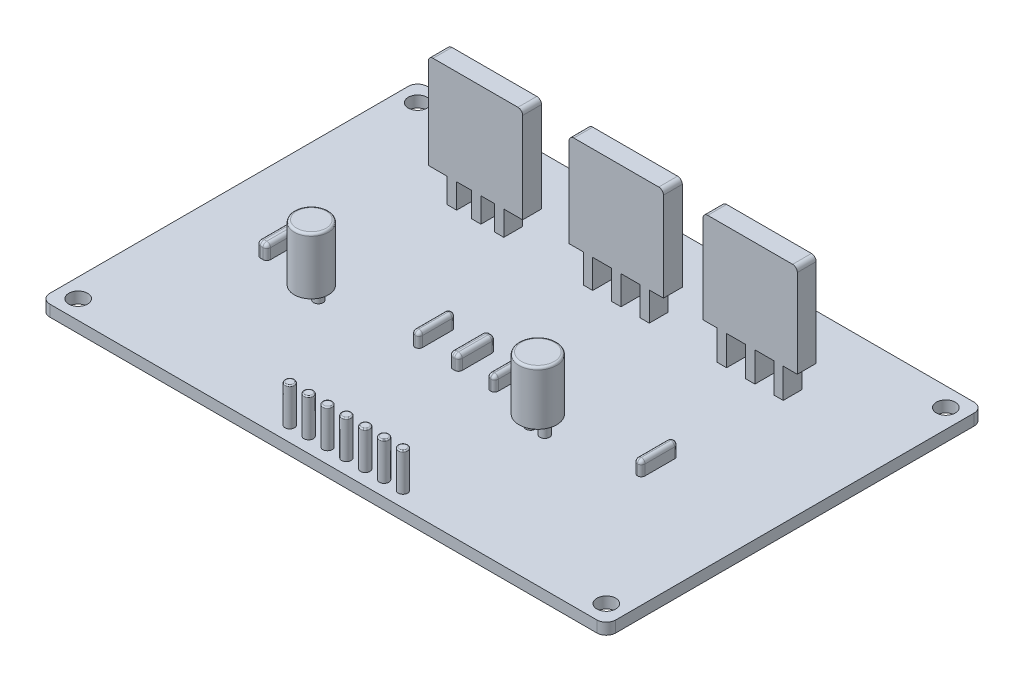
SolidWorks part; units mm, degrees
ref_plane "Front Plane" through (0, 0, 0) normal (0, 0, 1) x (1, 0, 0)
ref_plane "Top Plane" through (0, 0, 0) normal (0, 1, 0) x (1, 0, 0)
ref_plane "Right Plane" through (0, 0, 0) normal (1, 0, 0) x (0, 0, -1)
sketch "Sketch2" plane through (0, 0, 0) normal (0, 1, 0) x (1, 0, 0)
  line L1 (-30, -20) -> (30, -20)
  line L2 (-30, -20) -> (-30, 20)
  line L3 (-30, 20) -> (30, 20)
  line L4 (30, -20) -> (30, 20)
  line L5 (-30, -20) -> (30, 20) construction
  line L6 (-30, 20) -> (30, -20) construction
  point P0 (0, 0)
  dimension "D1" = 40
  dimension "D2" = 60
extrude "Boss-Extrude1" add sketch "Sketch2" along normal blind 1.2
sketch "Sketch3" plane through (0, 1.2, 0) normal (0, 1, 0) x (1, 0, 0)
  line L0 (-30, -20) -> (30, -20) construction
  line L1 (-30, 20) -> (-30, -20) construction
  line L2 (30, 20) -> (-30, 20) construction
  line L3 (30, -20) -> (30, 20) construction
  line L4 (30, 20) -> (-30, 20) construction
  circle A0 centre (-28, -18) radius 1
  circle A1 centre (-28, 18) radius 1
  circle A2 centre (28, 18) radius 1
  circle A3 centre (28, -18) radius 1
  dimension "D1" = 2
  dimension "D3" = 2
  dimension "D2" = 2
  dimension "D4" = 2
  dimension "D5" = 2
  dimension "D6" = 2
  dimension "D7" = 2
  dimension "D8" = 2
extrude "Cut-Extrude1" cut sketch "Sketch3" against normal blind 2
sketch "Sketch4" plane through (0, 1.2, 0) normal (0, 1, 0) x (1, 0, 0)
  line L1 (-19.065, 12.1957) -> (-9.065, 12.1957)
  line L2 (-19.065, 12.1957) -> (-19.065, 10.1957)
  line L3 (-19.065, 10.1957) -> (-9.065, 10.1957)
  line L4 (-9.065, 12.1957) -> (-9.065, 10.1957)
  line L5 (-19.065, 12.1957) -> (-9.065, 10.1957) construction
  line L6 (-19.065, 10.1957) -> (-9.065, 12.1957) construction
  point P0 (-14.065, 11.1957)
  dimension "D1" = 2
  dimension "D2" = 10
extrude "Boss-Extrude2" add sketch "Sketch4" along normal blind 12.6957 contours L3 L4 L1 L2
sketch "Sketch5" plane through (0, 0, -10.1957) normal (0, 0, 1) x (1, 0, 0)
  line L0 (-19.065, 1.2) -> (-9.065, 1.2) construction
  line L1 (-19.065, 1.2) -> (-17.065, 1.2)
  line L2 (-19.065, 1.2) -> (-19.065, 3.8072)
  line L3 (-19.065, 3.8072) -> (-17.065, 3.8072)
  line L4 (-17.065, 1.2) -> (-17.065, 3.8072)
  line L5 (-9.065, 1.2) -> (-11.065, 1.2)
  line L6 (-9.065, 1.2) -> (-9.065, 3.8072)
  line L7 (-9.065, 3.8072) -> (-11.065, 3.8072)
  line L8 (-11.065, 1.2) -> (-11.065, 3.8072)
  line L9 (-16.065, 3.8072) -> (-14.4903, 3.8072)
  line L10 (-16.065, 3.8072) -> (-16.065, 1.2)
  line L11 (-16.065, 1.2) -> (-14.4903, 1.2)
  line L12 (-14.4903, 3.8072) -> (-14.4903, 1.2)
  line L14 (-13.4903, 3.8072) -> (-12.065, 3.8072)
  line L15 (-13.4903, 3.8072) -> (-13.4903, 1.2)
  line L16 (-13.4903, 1.2) -> (-12.065, 1.2)
  line L17 (-12.065, 3.8072) -> (-12.065, 1.2)
  dimension "D1" = 1
  dimension "D2" = 1
  dimension "D3" = 1
  dimension "D4" = 2
  dimension "D5" = 2
extrude "Cut-Extrude2" cut sketch "Sketch5" against normal blind 3
sketch "Sketch6" plane through (0, 1.2, 0) normal (0, 1, 0) x (1, 0, 0)
  line L2 (-3.9751, 10.0333) -> (6.0249, 10.0333)
  line L3 (-3.9751, 10.0333) -> (-3.9751, 12.0333)
  line L4 (-3.9751, 12.0333) -> (6.0249, 12.0333)
  line L5 (6.0249, 10.0333) -> (6.0249, 12.0333)
  line L6 (10.2218, 10.0333) -> (20.2218, 10.0333)
  line L7 (10.2218, 10.0333) -> (10.2218, 12.0333)
  line L8 (10.2218, 12.0333) -> (20.2218, 12.0333)
  line L9 (20.2218, 10.0333) -> (20.2218, 12.0333)
  dimension "D1" = 2
  dimension "D2" = 10
  dimension "D3" = 2
  dimension "D4" = 10
extrude "Boss-Extrude3" add sketch "Sketch6" along normal blind 13 contours L6 L9 L8 L7 | L2 L5 L4 L3
sketch "Sketch7" plane through (0, 0, -10.0333) normal (0, 0, 1) x (1, 0, 0)
  line L0 (-3.9751, 1.2) -> (6.0249, 1.2) construction
  line L1 (-3.9751, 1.2) -> (-2.4751, 1.2)
  line L2 (-3.9751, 1.2) -> (-3.9751, 4.2459)
  line L3 (-3.9751, 4.2459) -> (-2.4751, 4.2459)
  line L4 (-2.4751, 1.2) -> (-2.4751, 4.2459)
  line L5 (-3.9751, 14.2) -> (-3.9751, 1.2) construction
  line L7 (6.0249, 1.2) -> (4.5249, 1.2)
  line L8 (6.0249, 1.2) -> (6.0249, 4.2459)
  line L9 (6.0249, 4.2459) -> (4.5249, 4.2459)
  line L10 (4.5249, 1.2) -> (4.5249, 4.2459)
  line L11 (-1.4751, 1.2) -> (0.5249, 1.2)
  line L12 (-1.4751, 1.2) -> (-1.4751, 4.2459)
  line L13 (-1.4751, 4.2459) -> (0.5249, 4.2459)
  line L14 (0.5249, 1.2) -> (0.5249, 4.2459)
  line L15 (1.5249, 1.2) -> (3.5249, 1.2)
  line L16 (1.5249, 1.2) -> (1.5249, 4.2459)
  line L17 (1.5249, 4.2459) -> (3.5249, 4.2459)
  line L18 (3.5249, 1.2) -> (3.5249, 4.2459)
  dimension "D1" = 1
  dimension "D2" = 1
  dimension "D3" = 1
  dimension "D4" = 1.5
  dimension "D5" = 1.5
  dimension "D6" = 2
  dimension "D7" = 2
extrude "Cut-Extrude3" cut sketch "Sketch7" against normal blind 3 contours L9 L10 L7 L8 | L13 L14 L11 L12 | L3 L4 L1 L2 | L17 L18 L15 L16
sketch "Sketch8" plane through (0, 0, -10.0333) normal (0, 0, 1) x (1, 0, 0)
  line L0 (10.2218, 1.2) -> (20.2218, 1.2) construction
  line L1 (10.2218, 1.2) -> (11.7218, 1.2)
  line L2 (10.2218, 1.2) -> (10.2218, 4.3532)
  line L3 (10.2218, 4.3532) -> (11.7218, 4.3532)
  line L4 (11.7218, 1.2) -> (11.7218, 4.3532)
  line L5 (20.2218, 1.2) -> (18.7218, 1.2)
  line L6 (20.2218, 1.2) -> (20.2218, 4.3532)
  line L7 (20.2218, 4.3532) -> (18.7218, 4.3532)
  line L8 (18.7218, 1.2) -> (18.7218, 4.3532)
  line L9 (17.7218, 1.2) -> (15.7218, 1.2)
  line L10 (17.7218, 1.2) -> (17.7218, 4.3532)
  line L11 (17.7218, 4.3532) -> (15.7218, 4.3532)
  line L12 (15.7218, 1.2) -> (15.7218, 4.3532)
  line L14 (14.7218, 1.2) -> (12.7218, 1.2)
  line L15 (14.7218, 1.2) -> (14.7218, 4.3532)
  line L16 (14.7218, 4.3532) -> (12.7218, 4.3532)
  line L17 (12.7218, 1.2) -> (12.7218, 4.3532)
  dimension "D1" = 1.5
  dimension "D2" = 1
  dimension "D3" = 1
  dimension "D4" = 1
  dimension "D5" = 2
  dimension "D6" = 2
extrude "Cut-Extrude4" cut sketch "Sketch8" against normal blind 3
sketch "Sketch9" plane through (0, 1.2, 0) normal (0, 1, 0) x (1, 0, 0)
  circle A0 centre (-16.6457, -5.3882) radius 0.5
  circle A1 centre (-15.1457, -5.3882) radius 0.5
  dimension "D1" = 1.5
extrude "Boss-Extrude5" add sketch "Sketch9" along normal blind 1
sketch "Sketch10" plane through (0, 2.2, 0) normal (0, 1, 0) x (1, 0, 0)
  circle A0 centre (-15.8957, -5.3772) radius 1.8145
extrude "Boss-Extrude6" add sketch "Sketch10" along normal blind 6
sketch "Sketch11" plane through (0, 1.2, 0) normal (0, 1, 0) x (1, 0, 0)
  circle A0 centre (7.7199, -5.7474) radius 0.5
  circle A1 centre (9.2199, -5.7474) radius 0.5
  dimension "D1" = 1.5
extrude "Boss-Extrude7" add sketch "Sketch11" along normal blind 1.5
sketch "Sketch12" plane through (0, 2.7, 0) normal (0, 1, 0) x (1, 0, 0)
  circle A0 centre (8.4536, -5.7145) radius 2
extrude "Boss-Extrude9" add sketch "Sketch12" along normal blind 5.7
sketch "Sketch13" plane through (0, 1.2, 0) normal (0, 1, 0) x (1, 0, 0)
  circle A0 centre (-5.1698, -18.3916) radius 0.5
  circle A1 centre (-3.1698, -18.3916) radius 0.5
  circle A2 centre (-1.1698, -18.3916) radius 0.5
  circle A3 centre (0.8302, -18.3916) radius 0.5
  circle A4 centre (2.8302, -18.3916) radius 0.5
  circle A5 centre (4.8302, -18.3916) radius 0.5
  circle A6 centre (6.8302, -18.3916) radius 0.5
  dimension "D1" = 2
  dimension "D2" = 2
  dimension "D3" = 2
  dimension "D4" = 2
  dimension "D5" = 2
  dimension "D6" = 2
extrude "Boss-Extrude10" add sketch "Sketch13" along normal blind 4
fillet "Fillet1" radius 1 4 edges at (-30, 0.6, -20) (30, 0.6, -20) (30, 0.6, 20) (-30, 0.6, 20)
fillet "Fillet2" radius 0.5 6 edges at (20.2218, 14.2, -11.0333) (10.2218, 14.2, -11.0333) (6.0249, 14.2, -11.0333) (-3.9751, 14.2, -11.0333) (-9.065, 13.8957, -11.1957) (-19.065, 13.8957, -11.1957)
fillet "Fillet3" radius 0.25 2 edges at (8.4536, 8.4, 7.7145) (-15.8957, 8.2, 7.1917)
fillet "Fillet4" radius 0.125 7 edges at (6.8302, 5.2, 18.8916) (4.8302, 5.2, 18.8916) (2.8302, 5.2, 18.8916) (0.8302, 5.2, 18.8916) (-1.1698, 5.2, 18.8916) (-3.1698, 5.2, 18.8916) (-5.1698, 5.2, 18.8916)
sketch "Sketch14" plane through (0, 1.2, 0) normal (0, 1, 0) x (1, 0, 0)
  line L1 (-6.0591, -0.694) -> (-5.2581, -0.694)
  line L2 (-6.0591, -0.694) -> (-6.0591, -4.6185)
  line L3 (-6.0591, -4.6185) -> (-5.2581, -4.6185)
  line L4 (-5.2581, -0.694) -> (-5.2581, -4.6185)
  line L5 (-2.0558, -0.694) -> (-1.0494, -0.694)
  line L6 (-2.0558, -0.694) -> (-2.0558, -4.6185)
  line L7 (-2.0558, -4.6185) -> (-1.0494, -4.6185)
  line L8 (-1.0494, -0.694) -> (-1.0494, -4.6185)
  line L9 (1.9334, -0.694) -> (2.7703, -0.694)
  line L10 (1.9334, -0.694) -> (1.9334, -4.6185)
  line L11 (1.9334, -4.6185) -> (2.7703, -4.6185)
  line L12 (2.7703, -0.694) -> (2.7703, -4.6185)
  line L13 (17.5246, -0.694) -> (18.3303, -0.694)
  line L14 (17.5246, -0.694) -> (17.5246, -4.6185)
  line L15 (17.5246, -4.6185) -> (18.3303, -4.6185)
  line L16 (18.3303, -0.694) -> (18.3303, -4.6185)
  line L17 (-22.4643, -0.694) -> (-21.3841, -0.694)
  line L18 (-22.4643, -0.694) -> (-22.4643, -4.6185)
  line L19 (-22.4643, -4.6185) -> (-21.3841, -4.6185)
  line L20 (-21.3841, -0.694) -> (-21.3841, -4.6185)
extrude "Boss-Extrude11" add sketch "Sketch14" along normal blind 1.5
fillet "Fillet5" radius 0.4 8 edges at (17.9274, 2.7, 0.694) (18.3303, 2.7, 2.6563) (17.9274, 2.7, 4.6185) (17.5246, 2.7, 2.6563) (17.5246, 1.95, 4.6185) (18.3303, 1.95, 4.6185) (17.5246, 1.95, 0.694) (18.3303, 1.95, 0.694)
fillet "Fillet6" radius 0.4 32 edges at (-21.9242, 2.7, 0.694) (-21.3841, 2.7, 2.6563) (-21.9242, 2.7, 4.6185) (-22.4643, 2.7, 2.6563) (-5.6586, 2.7, 0.694) (-5.2581, 2.7, 2.6563) (-5.6586, 2.7, 4.6185) (-6.0591, 2.7, 2.6563) (-1.5526, 2.7, 0.694) (-1.0494, 2.7, 2.6563) (-1.5526, 2.7, 4.6185) (-2.0558, 2.7, 2.6563) (2.3518, 2.7, 0.694) (2.7703, 2.7, 2.6563) (2.3518, 2.7, 4.6185) (1.9334, 2.7, 2.6563) (2.7703, 1.95, 4.6185) (1.9334, 1.95, 4.6185) (2.7703, 1.95, 0.694) (1.9334, 1.95, 0.694) (-1.0494, 1.95, 4.6185) (-2.0558, 1.95, 4.6185) (-1.0494, 1.95, 0.694) (-2.0558, 1.95, 0.694) (-6.0591, 1.95, 0.694) (-5.2581, 1.95, 0.694) (-5.2581, 1.95, 4.6185) (-6.0591, 1.95, 4.6185) (-22.4643, 1.95, 0.694) (-21.3841, 1.95, 0.694) (-21.3841, 1.95, 4.6185) (-22.4643, 1.95, 4.6185)
